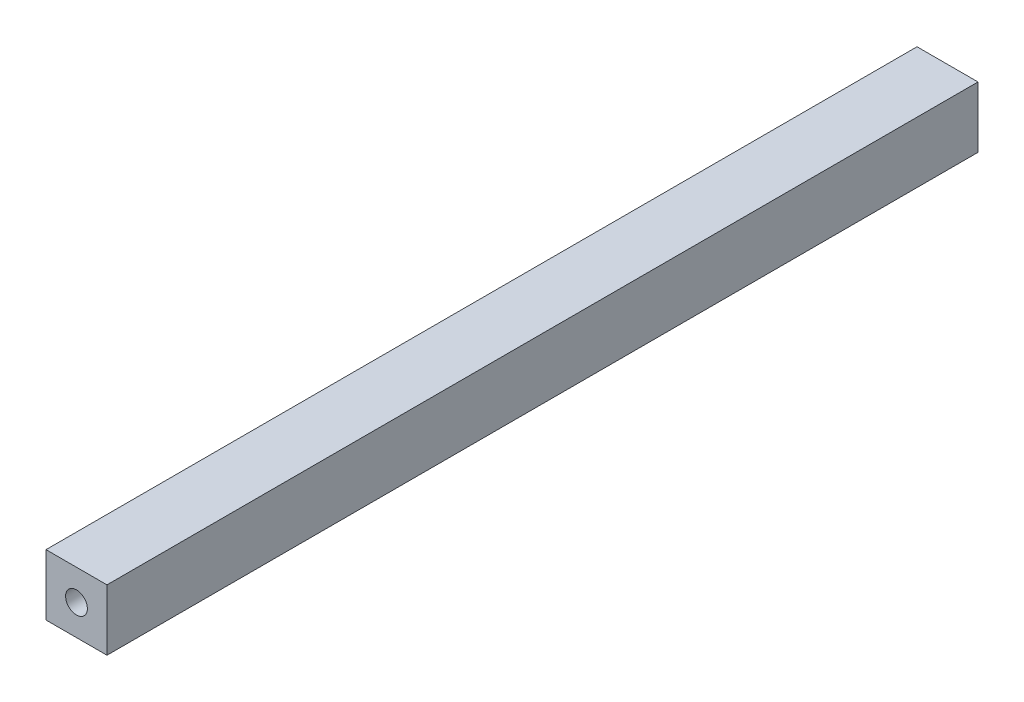
SolidWorks part; units mm, degrees
material "Plain Carbon Steel"
ref_plane "Front Plane" through (0, 0, 0) normal (0, 0, 1) x (1, 0, 0)
ref_plane "Top Plane" through (0, 0, 0) normal (0, 1, 0) x (1, 0, 0)
ref_plane "Right Plane" through (0, 0, 0) normal (1, 0, 0) x (0, 0, -1)
sketch "Sketch1" plane through (0, 0, 0) normal (0, 0, 1) x (1, 0, 0)
  line L1 (-17.78, 17.78) -> (17.78, 17.78)
  line L2 (-17.78, 17.78) -> (-17.78, -17.78)
  line L3 (-17.78, -17.78) -> (17.78, -17.78)
  line L4 (17.78, 17.78) -> (17.78, -17.78)
  line L5 (-17.78, 17.78) -> (17.78, -17.78) construction
  line L6 (-17.78, -17.78) -> (17.78, 17.78) construction
  point P0 (0, 0)
  dimension "D1" = 35.56
  dimension "D2" = 35.56
extrude "Boss-Extrude1" add sketch "Sketch1" along normal blind 508
sketch "Sketch2" plane through (0, 0, 508) normal (0, 0, 1) x (1, 0, 0)
  circle A0 centre (0, 0) radius 6.35
  dimension "D1" = 12.7
extrude "Cut-Extrude1" cut sketch "Sketch2" against normal through all
